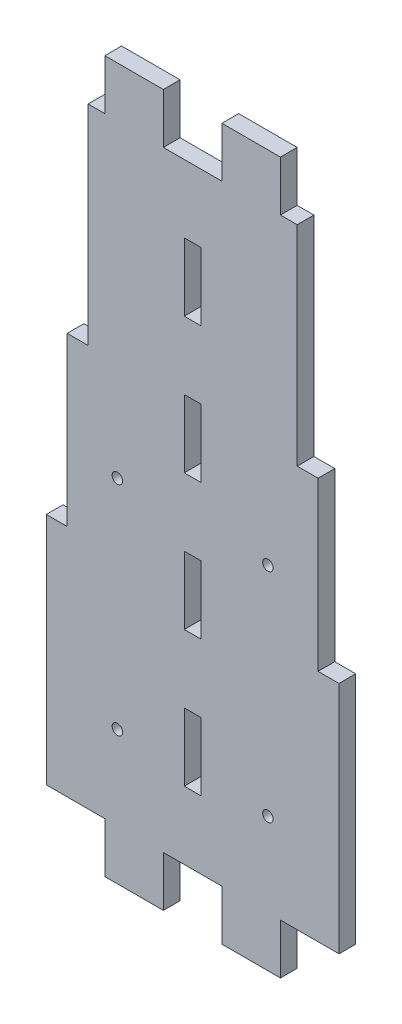
SolidWorks part; units mm, degrees
material "Beech"
ref_plane "Front Plane" through (0, 0, 0) normal (0, 0, 1) x (1, 0, 0)
ref_plane "Top Plane" through (0, 0, 0) normal (0, 1, 0) x (1, 0, 0)
ref_plane "Right Plane" through (0, 0, 0) normal (1, 0, 0) x (0, 0, -1)
sketch "Sketch1" plane through (0, 0, 0) normal (0, 0, 1) x (1, 0, 0)
  line L0 (0, 0) -> (17.78, 0)
  line L1 (17.78, 0) -> (17.78, 15.24)
  line L2 (17.78, 15.24) -> (35.56, 15.24)
  line L3 (35.56, 15.24) -> (35.56, 0)
  line L4 (35.56, 0) -> (53.34, 0)
  line L5 (53.34, 0) -> (53.34, 15.24)
  line L6 (53.34, 15.24) -> (71.12, 15.24)
  line L7 (71.12, 15.24) -> (71.12, 0)
  line L8 (71.12, 0) -> (88.9, 0)
  line L9 (88.9, 0) -> (88.9, -185.42)
  line L10 (0, 0) -> (0, -185.42)
  line L11 (88.9, -92.71) -> (0, -92.71) construction
  line L12 (0, -185.42) -> (17.78, -185.42)
  line L13 (71.12, -185.42) -> (88.9, -185.42)
  line L14 (71.12, -200.66) -> (71.12, -185.42)
  line L15 (53.34, -200.66) -> (71.12, -200.66)
  line L16 (53.34, -185.42) -> (53.34, -200.66)
  line L17 (35.56, -185.42) -> (53.34, -185.42)
  line L18 (35.56, -200.66) -> (35.56, -185.42)
  line L19 (17.78, -200.66) -> (35.56, -200.66)
  line L20 (17.78, -185.42) -> (17.78, -200.66)
  point P15 (0, 0)
  dimension "D1" = 185.42
  dimension "D2" = 88.9
  dimension "D3" = 15.24
extrude "Boss-Extrude1" add sketch "Sketch1" along normal blind 5.08
sketch "Sketch2" plane through (0, 0, 5.08) normal (0, 0, 1) x (1, 0, 0)
  line L0 (35.56, -185.42) -> (53.34, -185.42) construction
  line L1 (21.59, -160.02) -> (67.31, -160.02) construction
  line L2 (21.59, -160.02) -> (21.59, -93.98) construction
  line L3 (21.59, -93.98) -> (67.31, -93.98) construction
  line L4 (67.31, -160.02) -> (67.31, -93.98) construction
  line L5 (21.59, -160.02) -> (67.31, -93.98) construction
  line L6 (21.59, -93.98) -> (67.31, -160.02) construction
  line L7 (53.34, 0) -> (35.56, 0) construction
  circle A0 centre (21.59, -93.98) radius 1.5875
  circle A1 centre (67.31, -93.98) radius 1.5875
  circle A2 centre (67.31, -160.02) radius 1.5875
  circle A3 centre (21.59, -160.02) radius 1.5875
  point P0 (44.45, -127)
  point P10 (44.45, 0)
  dimension "D4" = 3.175
  dimension "D1" = 45.72
  dimension "D2" = 66.04
  dimension "D3" = 25.4
extrude "Cut-Extrude1" cut sketch "Sketch2" against normal through all
sketch "Sketch3" plane through (0, 0, 0) normal (0, 0, -1) x (-1, 0, 0)
  line L0 (-41.91, -20.6022) -> (-41.91, 0) construction
  line L1 (-46.99, -164.8178) -> (-41.91, -164.8178)
  line L2 (-46.99, -164.8178) -> (-46.99, -144.2156)
  line L3 (-46.99, -144.2156) -> (-41.91, -144.2156)
  line L4 (-41.91, -164.8178) -> (-41.91, -144.2156)
  line L5 (-46.99, -164.8178) -> (-41.91, -144.2156) construction
  line L6 (-46.99, -144.2156) -> (-41.91, -164.8178) construction
  line L7 (-46.99, -82.4089) -> (-41.91, -82.4089)
  line L8 (-46.99, -82.4089) -> (-46.99, -61.8067)
  line L9 (-46.99, -61.8067) -> (-41.91, -61.8067)
  line L10 (-41.91, -82.4089) -> (-41.91, -61.8067)
  line L11 (-46.99, -82.4089) -> (-41.91, -61.8067) construction
  line L12 (-46.99, -61.8067) -> (-41.91, -82.4089) construction
  line L13 (-46.99, -41.2044) -> (-41.91, -41.2044)
  line L14 (-46.99, -41.2044) -> (-46.99, -20.6022)
  line L15 (-46.99, -20.6022) -> (-41.91, -20.6022)
  line L16 (-41.91, -41.2044) -> (-41.91, -20.6022)
  line L17 (-46.99, -41.2044) -> (-41.91, -20.6022) construction
  line L18 (-46.99, -20.6022) -> (-41.91, -41.2044) construction
  line L19 (-46.99, -123.6133) -> (-41.91, -123.6133)
  line L20 (-46.99, -123.6133) -> (-46.99, -103.0111)
  line L21 (-46.99, -103.0111) -> (-41.91, -103.0111)
  line L22 (-41.91, -123.6133) -> (-41.91, -103.0111)
  line L23 (-46.99, -123.6133) -> (-41.91, -103.0111) construction
  line L24 (-46.99, -103.0111) -> (-41.91, -123.6133) construction
  line L25 (-53.34, 0) -> (-35.56, 0) construction
  line L27 (-41.91, -61.8067) -> (-41.91, -41.2044) construction
  line L28 (-41.91, -82.4089) -> (-41.91, -103.0111) construction
  line L29 (-41.91, -144.2156) -> (-41.91, -123.6133) construction
  line L30 (-41.91, -164.8178) -> (-41.91, -185.42) construction
  line L31 (-35.56, -185.42) -> (-53.34, -185.42) construction
  point P0 (-44.45, -154.5167)
  point P5 (-44.45, -72.1078)
  point P10 (-44.45, -30.9033)
  point P15 (-44.45, -113.3122)
  point P26 (-41.0813, -15.8292)
  point P27 (0, 0)
  point P28 (-44.45, 0)
  point P29 (0, 0)
  dimension "D1" = 5.08
extrude "Cut-Extrude2" cut sketch "Sketch3" against normal through all
sketch "Sketch4" plane through (0, 0, 0) normal (0, 0, -1) x (-1, 0, 0)
  line L0 (-88.9, -185.42) -> (-88.9, 0) construction
  line L1 (-88.9, 0) -> (-76.2, 0)
  line L2 (-88.9, 0) -> (-88.9, -63.5)
  line L3 (-88.9, -63.5) -> (-76.2, -63.5) construction
  line L4 (-76.2, 0) -> (-76.2, -63.5)
  line L5 (-88.9, -114.3) -> (-82.55, -114.3)
  line L6 (-88.9, -114.3) -> (-88.9, -63.5)
  line L7 (-88.9, -63.5) -> (-82.55, -63.5) construction
  line L8 (-82.55, -114.3) -> (-82.55, -63.5)
  line L9 (-82.55, -63.5) -> (-76.2, -63.5)
  line L10 (-44.45, 0) -> (-44.45, -185.42) construction
  line L11 (-53.34, 0) -> (-35.56, 0) construction
  line L12 (-35.56, -185.42) -> (-53.34, -185.42) construction
  line L13 (0, -63.5) -> (-6.35, -63.5) construction
  line L14 (0, -63.5) -> (-12.7, -63.5) construction
  line L15 (-6.35, -63.5) -> (-12.7, -63.5)
  line L16 (-6.35, -114.3) -> (-6.35, -63.5)
  line L17 (0, -114.3) -> (0, -63.5)
  line L18 (0, -114.3) -> (-6.35, -114.3)
  line L19 (-12.7, 0) -> (-12.7, -63.5)
  line L20 (0, 0) -> (0, -63.5)
  line L21 (0, 0) -> (-12.7, 0)
  dimension "D1" = 63.5
  dimension "D2" = 50.8
  dimension "D3" = 12.7
extrude "Cut-Extrude3" cut sketch "Sketch4" against normal through all
